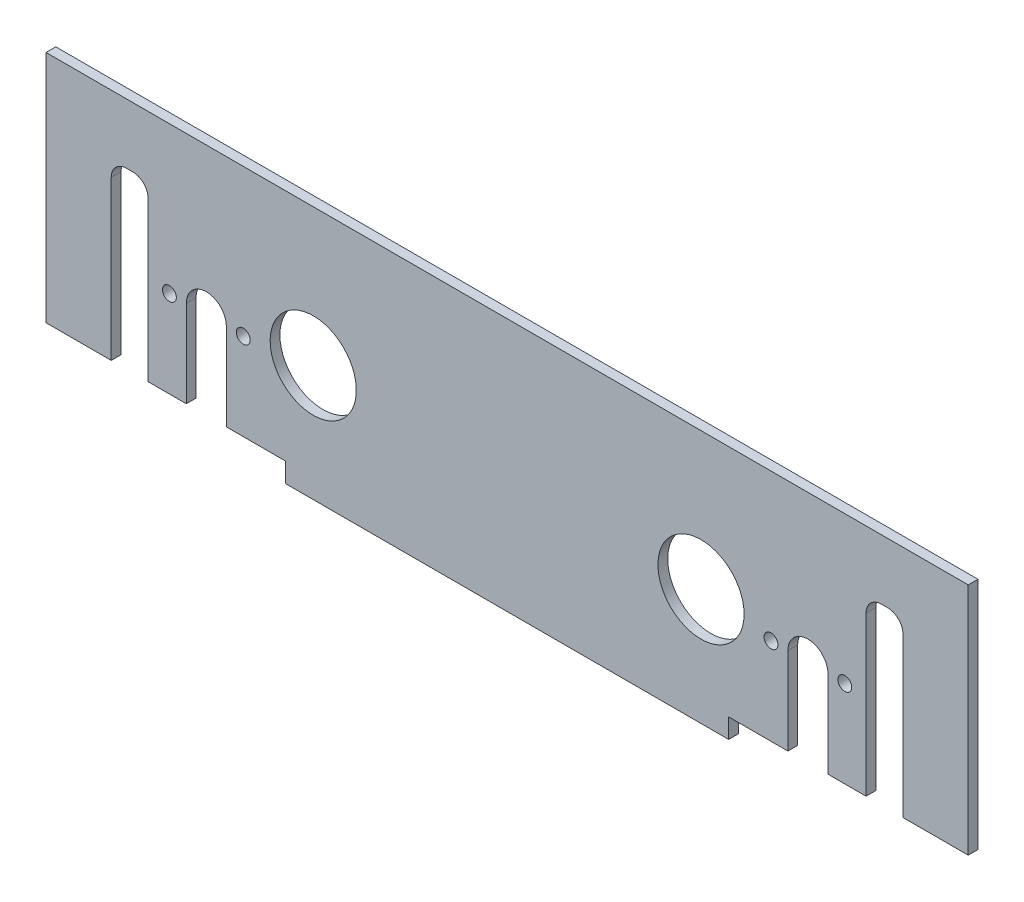
SolidWorks part; units mm, degrees
material "ABS"
ref_plane "X-Y Datum" through (0, 0, 0) normal (0, 0, 1) x (1, 0, 0)
ref_plane "X-Z Datum" through (0, 0, 0) normal (0, 1, 0) x (1, 0, 0)
ref_plane "Y-Z Datum" through (0, 0, 0) normal (1, 0, 0) x (0, 0, -1)
sketch "Sketch1" plane through (0, 0, 0) normal (0, 0, 1) x (1, 0, 0)
  line L1 (-149.85, 38.0375) -> (149.85, 38.0375)
  line L2 (-149.85, 38.0375) -> (-149.85, -38.0375)
  line L3 (-149.85, -38.0375) -> (149.85, -38.0375)
  line L4 (149.85, 38.0375) -> (149.85, -38.0375)
  line L5 (-149.85, 38.0375) -> (149.85, -38.0375) construction
  line L6 (-149.85, -38.0375) -> (149.85, 38.0375) construction
  point P0 (0, 0)
  dimension "D1" = 76.075
  dimension "D2" = 299.7
extrude "Boss-Extrude1" add sketch "Sketch1" along normal blind 3.175
sketch "Sketch3" plane through (0, 0, 0) normal (0, 0, -1) x (-1, 0, 0)
  line L3 (149.85, -38.0375) -> (-149.85, -38.0375) construction
  line L4 (149.85, -38.0375) -> (-149.85, -38.0375)
  line L5 (-104.25, -9.7625) -> (-104.25, -38.0375)
  line L6 (-91.25, -9.7625) -> (-91.25, -38.0375)
  line L7 (104.25, -9.7625) -> (104.25, -38.0375)
  line L8 (91.25, -9.7625) -> (91.25, -38.0375)
  circle A6 centre (-97.75, -9.7625) radius 6.5
  circle A7 centre (97.75, -9.7625) radius 6.5
  point P0 (97.75, -9.7625)
  point P1 (-97.75, -9.7625)
  point P16 (109.75, -9.7625)
  point P17 (85.75, -9.7625)
  point P18 (-85.75, -9.7625)
  point P19 (-109.75, -9.7625)
  dimension "D1" = 13
sketch "Sketch8" plane through (0, 0, 3.175) normal (0, 0, 1) x (1, 0, 0)
  line L0 (128.65, -27.2824) -> (128.65, -38.0375)
  line L1 (121.65, 18.5125) -> (123.65, 18.5125)
  line L3 (-149.85, -38.0375) -> (149.85, -38.0375) construction
  line L4 (122.65, -32.2824) -> (122.65, 18.5125) construction
  line L5 (121.65, -32.2824) -> (123.65, -32.2824)
  line L6 (116.65, -27.2824) -> (116.65, 13.5125)
  line L8 (128.65, -27.2824) -> (128.65, 13.5125)
  line L9 (116.65, -32.2824) -> (128.65, 18.5125) construction
  line L10 (116.65, 18.5125) -> (128.65, -32.2824) construction
  line L12 (116.65, -27.2824) -> (116.65, -38.0375)
  line L13 (-149.85, -38.0375) -> (149.85, -38.0375)
  line L15 (149.85, -38.0375) -> (149.85, 38.0375) construction
  arc A0 (121.65, -32.2824) -> (116.65, -27.2824) centre (121.65, -27.2824) cw
  arc A1 (123.65, -32.2824) -> (128.65, -27.2824) centre (123.65, -27.2824) ccw
  arc A2 (128.65, 13.5125) -> (123.65, 18.5125) centre (123.65, 13.5125) ccw
  arc A3 (121.65, 18.5125) -> (116.65, 13.5125) centre (121.65, 13.5125) ccw
  point P0 (122.65, -6.885)
  line M25 (-149.85, -38.0375) -> (149.85, -38.0375)
  dimension "D1" = 5
  dimension "D2" = 27.2
  dimension "D3" = 31.1525
  dimension "D4" = 12
extrude "Cut-Extrude4" cut sketch "Sketch8" against normal through all contours L1 A3 L6 A0 L5 A1 L8 A2 | A1 L5 A0 L12 L0 M25
mirror "Mirror3" about plane through (0, 0, 0) normal (1, 0, 0) of "Cut-Extrude4"
extrude "Cut-Extrude5" cut sketch "Sketch3" against normal through all contours A6 | A6 L5 L4 L6 | A7 | A7 L8 L4 L7
hole_wizard "M4 Clearance Hole1" positions "Sketch11" profile "Sketch10" hole size "M4" standard "ANSI Metric" end condition through all
sketch "Sketch11" plane through (0, 0, 0) normal (0, 0, -1) x (-1, 0, 0)
  point P0 (-85.75, -9.7625)
  point P3 (-109.75, -9.7625)
  point P6 (109.75, -9.7625)
  point P9 (85.75, -9.7625)
sketch "Sketch10" plane through (85.75, -9.7625, 0) normal (1, 0, 0) x (0, 1, 0)
  line L0 (0, 0) -> (0, 3.175)
  line L1 (0, 3.175) -> (2.25, 3.175)
  line L2 (2.25, 3.175) -> (2.25, 0)
  line L5 (2.25, 0) -> (0, 0)
  line L11 (0, -6.35) -> (0, 107.95) construction
  dimension "Thru Hole Dia." = 4.5
  dimension "Thru Hole Depth" = 3.175
sketch "Sketch12" plane through (0, -38.0375, 0) normal (0, -1, 0) x (1, 0, 0)
  line L0 (0, 0) -> (0, 3.175) construction
  line L1 (-91.25, 0) -> (91.25, 0) construction
  line L2 (-91.25, 3.175) -> (91.25, 3.175) construction
  line L4 (-72, 3.175) -> (72, 3.175)
  line L5 (-72, 3.175) -> (-72, 0)
  line L6 (-72, 0) -> (72, 0)
  line L7 (72, 3.175) -> (72, 0)
  line L8 (-72, 3.175) -> (72, 0) construction
  line L9 (-72, 0) -> (72, 3.175) construction
  point P6 (0, 1.5875)
  dimension "D1" = 144
extrude "Boss-Extrude2" add sketch "Sketch12" along normal blind 6.35
sketch "Sketch13" plane through (0, 0, 0) normal (0, 0, -1) x (-1, 0, 0)
  line L0 (65.2939, -6.6447) -> (60.7239, -6.6447) construction
  line L1 (65.2939, -2.7997) -> (65.2939, -10.4897) construction
  line L2 (60.7239, -10.7897) -> (60.7239, -2.4997) construction
  circle A0 centre (63.0089, -6.6447) radius 14
  dimension "D1" = 28
extrude "Cut-Extrude6" cut sketch "Sketch13" against normal through all
mirror "Mirror4" about plane through (0, 0, 0) normal (1, 0, 0) of "Cut-Extrude6"
